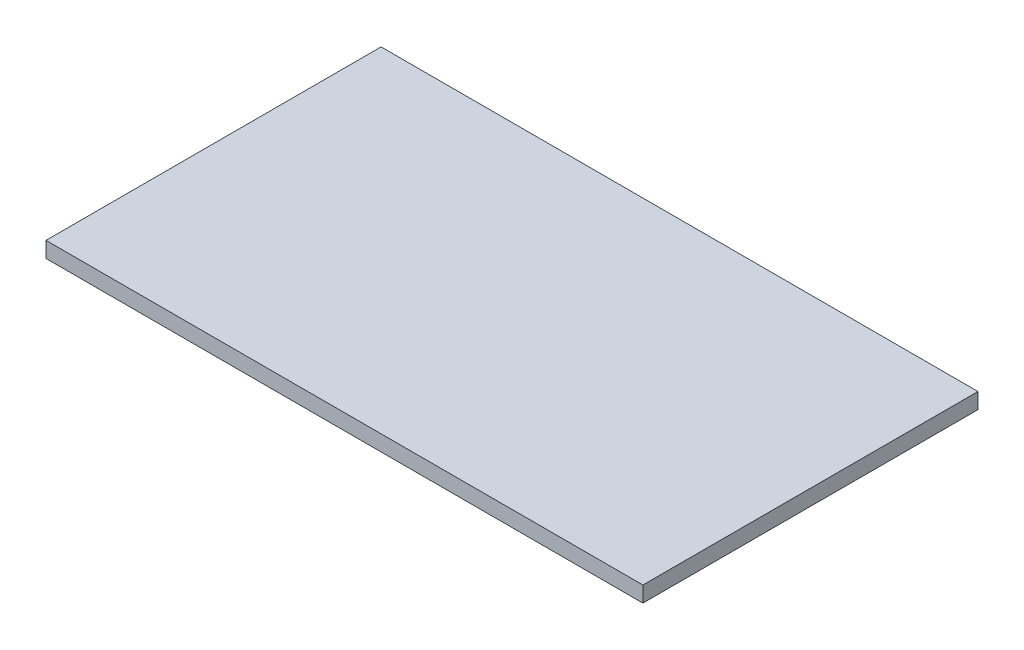
SolidWorks part; units mm, degrees
ref_plane "Front Plane" through (0, 0, 0) normal (0, 0, 1) x (1, 0, 0)
ref_plane "Top Plane" through (0, 0, 0) normal (0, 1, 0) x (1, 0, 0)
ref_plane "Right Plane" through (0, 0, 0) normal (1, 0, 0) x (0, 0, -1)
sketch "Sketch1" plane through (0, 0, 0) normal (0, 1, 0) x (1, 0, 0)
  line L1 (-28.5, 16) -> (28.5, 16)
  line L2 (-28.5, 16) -> (-28.5, -16)
  line L3 (-28.5, -16) -> (28.5, -16)
  line L4 (28.5, 16) -> (28.5, -16)
  line L5 (-28.5, 16) -> (28.5, -16) construction
  line L6 (-28.5, -16) -> (28.5, 16) construction
  point P0 (0, 0)
extrude "Boss-Extrude1" add sketch "Sketch1" along normal blind 1.5
